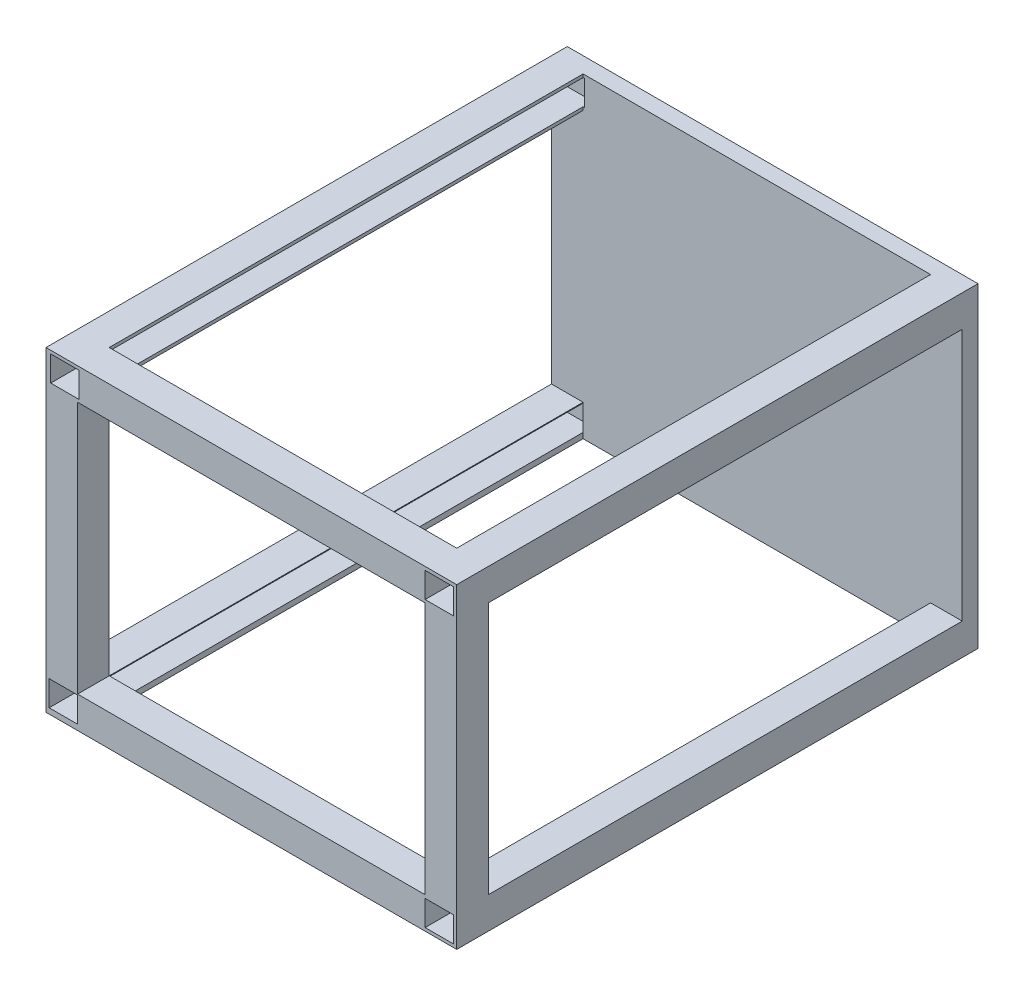
SolidWorks part; units mm, degrees
ref_plane "Front Plane" through (0, 0, 0) normal (0, 0, 1) x (1, 0, 0)
ref_plane "Top Plane" through (0, 0, 0) normal (0, 1, 0) x (1, 0, 0)
ref_plane "Right Plane" through (0, 0, 0) normal (1, 0, 0) x (0, 0, -1)
sketch "Sketch1" plane through (0, 0, 0) normal (0, 0, 1) x (1, 0, 0)
  line L1 (0, 0) -> (130, 0)
  line L2 (0, 0) -> (0, 100)
  line L3 (0, 100) -> (130, 100)
  line L4 (130, 0) -> (130, 100)
  dimension "D1" = 100
  dimension "D2" = 130
extrude "Boss-Extrude1" add sketch "Sketch1" along normal blind 5
sketch "Sketch2" plane through (0, 0, 5) normal (0, 0, 1) x (1, 0, 0)
  line L1 (0, 100) -> (10, 100)
  line L2 (0, 100) -> (0, 90)
  line L3 (0, 90) -> (10, 90)
  line L4 (10, 100) -> (10, 90)
  line L5 (130, 100) -> (120, 100)
  line L6 (130, 100) -> (130, 90)
  line L7 (130, 90) -> (120, 90)
  line L8 (120, 100) -> (120, 90)
  line L9 (0, 0) -> (10, 0)
  line L10 (0, 0) -> (0, 10)
  line L11 (0, 10) -> (10, 10)
  line L12 (10, 0) -> (10, 10)
  line L13 (130, 0) -> (120, 0)
  line L14 (130, 0) -> (130, 10)
  line L15 (130, 10) -> (120, 10)
  line L16 (120, 0) -> (120, 10)
  dimension "D1" = 10
  dimension "D2" = 10
  dimension "D3" = 10
  dimension "D4" = 10
  dimension "D5" = 10
  dimension "D6" = 10
  dimension "D7" = 10
  dimension "D8" = 10
extrude "Boss-Extrude2" add sketch "Sketch2" along normal blind 160
sketch "Sketch3" plane through (10, 0, 0) normal (1, 0, 0) x (0, 0, -1)
  line L1 (-165, 0) -> (-155, 0)
  line L2 (-165, 0) -> (-165, 10)
  line L3 (-165, 10) -> (-155, 10)
  line L4 (-155, 0) -> (-155, 10)
  dimension "D1" = 10
  dimension "D2" = 10
extrude "Boss-Extrude3" add sketch "Sketch3" along normal blind 110
sketch "Sketch4" plane through (10, 0, 0) normal (1, 0, 0) x (0, 0, -1)
  line L0 (-165, 100) -> (0, 100) construction
  line L1 (-165, 90) -> (-155, 90)
  line L2 (-165, 90) -> (-165, 100)
  line L3 (-165, 100) -> (-155, 100)
  line L4 (-155, 90) -> (-155, 100)
  dimension "D1" = 10
extrude "Boss-Extrude4" add sketch "Sketch4" along normal blind 110
sketch "Sketch5" plane through (0, 90, 0) normal (0, -1, 0) x (1, 0, 0)
  line L1 (10, 155) -> (0, 155)
  line L2 (10, 155) -> (10, 165)
  line L3 (10, 165) -> (0, 165)
  line L4 (0, 155) -> (0, 165)
extrude "Boss-Extrude5" add sketch "Sketch5" along normal blind 80
sketch "Sketch6" plane through (0, 90, 0) normal (0, -1, 0) x (1, 0, 0)
  line L1 (120, 155) -> (130, 155)
  line L2 (120, 155) -> (120, 165)
  line L3 (120, 165) -> (130, 165)
  line L4 (130, 155) -> (130, 165)
extrude "Boss-Extrude6" add sketch "Sketch6" along normal blind 80
sketch "Sketch9" plane through (0, 0, 165) normal (0, 0, 1) x (1, 0, 0)
  line L0 (130, 0) -> (130, 100) construction
  line L1 (120, 90.92) -> (129, 90.92)
  line L2 (120, 90.92) -> (120, 98.92)
  line L3 (120, 98.92) -> (129, 98.92)
  line L4 (129, 90.92) -> (129, 98.92)
  line L5 (120, 9) -> (129, 9)
  line L6 (120, 9) -> (120, 1)
  line L7 (120, 1) -> (129, 1)
  line L8 (129, 9) -> (129, 1)
  line L9 (1, 1.7415) -> (10, 1.7415)
  line L10 (1, 1.7415) -> (1, 9.7415)
  line L11 (1, 9.7415) -> (10, 9.7415)
  line L12 (10, 1.7415) -> (10, 9.7415)
  line L13 (10.4955, 91) -> (1.4955, 91)
  line L14 (10.4955, 91) -> (10.4955, 99)
  line L15 (10.4955, 99) -> (1.4955, 99)
  line L16 (1.4955, 91) -> (1.4955, 99)
  line L17 (0, 0) -> (130, 0) construction
  line L20 (0, 100) -> (0, 0) construction
  dimension "D1" = 9
  dimension "D2" = 8
  dimension "D3" = 10
  dimension "D4" = 8
  dimension "D5" = 9
  dimension "D6" = 10
  dimension "D7" = 1
  dimension "D8" = 8
  dimension "D9" = 9
  dimension "D10" = 10
  dimension "D11" = 9
  dimension "D12" = 8
  dimension "D13" = 99
extrude "Cut-Extrude4" cut sketch "Sketch9" against normal blind 163
